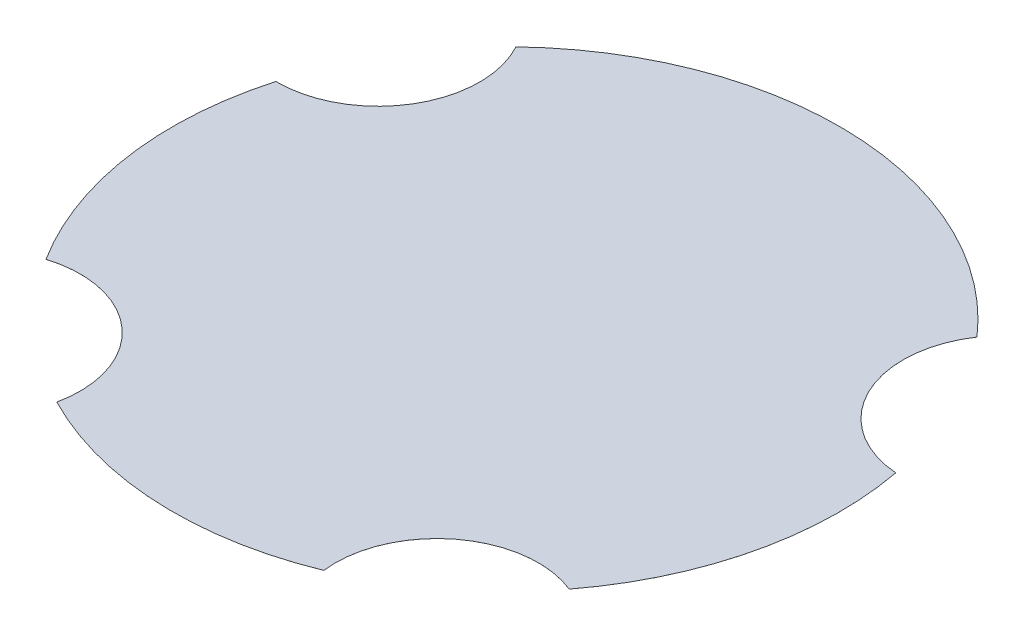
SolidWorks part; units mm, degrees
material "Pure Gold"
ref_plane "Front Plane" through (0, 0, 0) normal (0, 0, 1) x (1, 0, 0)
ref_plane "Top Plane" through (0, 0, 0) normal (0, 1, 0) x (1, 0, 0)
ref_plane "Right Plane" through (0, 0, 0) normal (1, 0, 0) x (0, 0, -1)
sketch "Sketch1" plane through (0, 0, 0) normal (0, 1, 0) x (-1, 0, 0)
  arc A1 (-23.5762, 25.8206) -> (-30.1414, -1.8777) centre (4.2545, 4.5968) ccw
  arc A2 (-23.5762, 25.8206) -> (-9.0018, 36.9893) centre (-19.5721, 35.6892) ccw
  arc A3 (20.2992, 35.7026) -> (33.8386, 23.2994) centre (30.7149, 33.481) ccw
  arc A4 (37.9376, -4.9135) -> (28.4877, -20.6569) centre (37.8406, -15.5631) ccw
  arc A5 (-22.0649, -18.4746) -> (-30.1414, -1.8777) centre (-30.9397, -12.5297) ccw
  arc A9 (20.2992, 35.7026) -> (-9.0018, 36.9893) centre (4.2545, 4.5968) ccw
  arc A10 (-22.0649, -18.4746) -> (28.4877, -20.6569) centre (4.2545, 4.5968) ccw
  arc A11 (37.9376, -4.9135) -> (33.8386, 23.2994) centre (4.2545, 4.5968) ccw
extrude "Boss-Extrude1" add sketch "Sketch1" along normal blind 0.001 contours A4 A11 A3 A9 A2 A1 A5 A10
